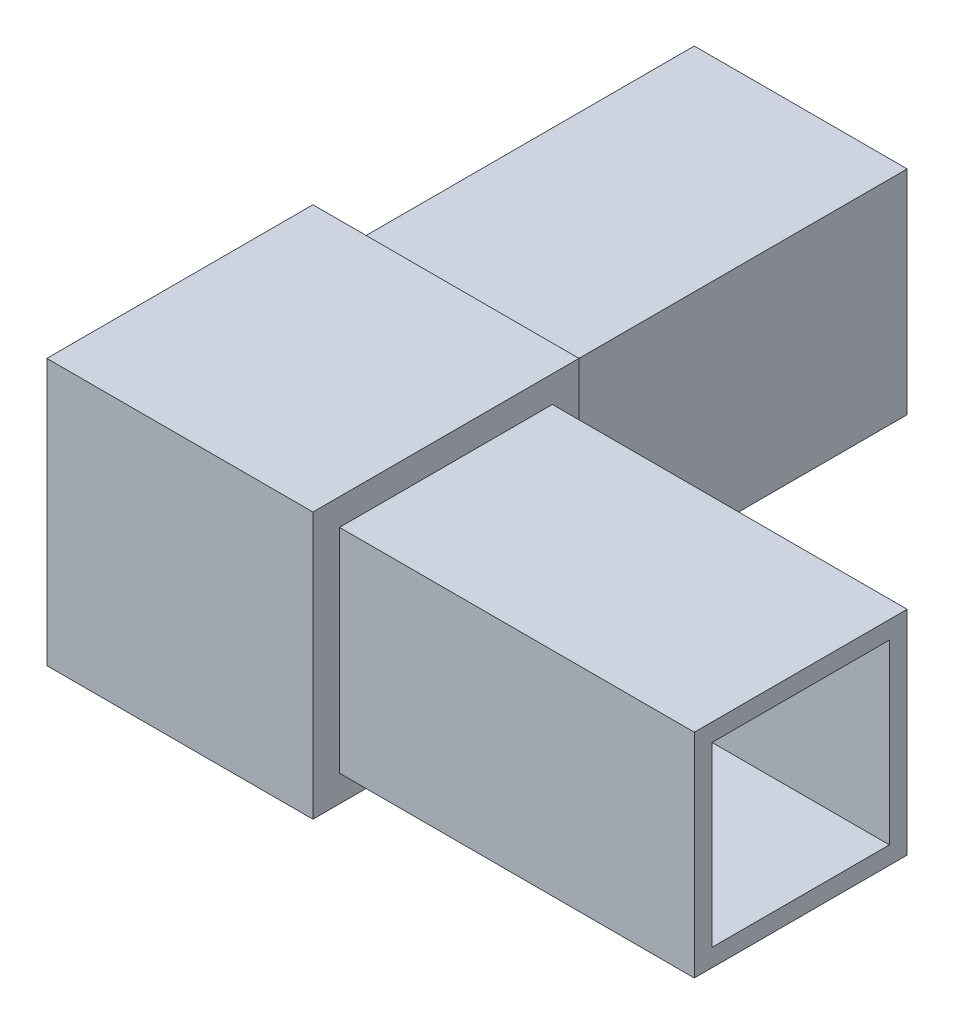
SolidWorks part; units mm, degrees
ref_plane "Alzado" through (0, 0, 0) normal (0, 0, 1) x (1, 0, 0)
ref_plane "Planta" through (0, 0, 0) normal (0, 1, 0) x (1, 0, 0)
ref_plane "Vista lateral" through (0, 0, 0) normal (1, 0, 0) x (0, 0, -1)
sketch "Croquis1" plane through (0, 0, 0) normal (0, 1, 0) x (1, 0, 0)
  line L1 (15, -15) -> (-15, -15)
  line L2 (15, -15) -> (15, 15)
  line L3 (15, 15) -> (-15, 15)
  line L4 (-15, -15) -> (-15, 15)
  line L5 (15, -15) -> (-15, 15) construction
  line L6 (15, 15) -> (-15, -15) construction
  line L7 (15, -15) -> (55, -15)
  line L8 (15, -15) -> (15, 15)
  line L9 (15, 15) -> (55, 15)
  line L10 (55, -15) -> (55, 15)
  line L11 (-15, 15) -> (15, 15)
  line L12 (-15, 15) -> (-15, 55)
  line L13 (-15, 55) -> (15, 55)
  line L14 (15, 15) -> (15, 55)
  point P0 (0, 0)
  dimension "D1" = 30
  dimension "D2" = 30
  dimension "D3" = 40
  dimension "D4" = 40
extrude "Extruir1" add sketch "Croquis1" along normal blind 30 contours L3 L14 L13 L12 | L4 L1 L2 L3 | L7 L10 L9 L2
sketch "Croquis2" plane through (55, 0, 0) normal (1, 0, 0) x (0, 0, -1)
  line L4 (-15, 0) -> (15, 0)
  line L5 (15, 0) -> (15, 30)
  line L6 (15, 30) -> (-15, 30)
  line L7 (-15, 30) -> (-15, 0)
  line L8 (-15, 0) -> (15, 0)
  line L9 (15, 0) -> (15, 30)
  line L10 (15, 30) -> (-15, 30)
  line L11 (-15, 30) -> (-15, 0)
  line L16 (-12, 3) -> (12, 3)
  line L17 (12, 3) -> (12, 27)
  line L18 (12, 27) -> (-12, 27)
  line L19 (-12, 27) -> (-12, 3)
  line L20 (-12, 3) -> (12, 3)
  line L21 (12, 3) -> (12, 27)
  line L22 (12, 27) -> (-12, 27)
  line L23 (-12, 27) -> (-12, 3)
  dimension "D1" = 0
  dimension "D2" = 3
extrude "Extruir2" cut sketch "Croquis2" against normal blind 40
sketch "Croquis3" plane through (0, 0, -55) normal (0, 0, -1) x (-1, 0, 0)
  line L0 (-12, 3) -> (12, 3)
  line L1 (12, 3) -> (12, 27)
  line L2 (12, 27) -> (-12, 27)
  line L3 (-12, 27) -> (-12, 3)
  line L4 (-15, 0) -> (15, 0)
  line L5 (15, 0) -> (15, 30)
  line L6 (15, 30) -> (-15, 30)
  line L7 (-15, 30) -> (-15, 0)
  line L8 (-15, 0) -> (15, 0)
  line L9 (15, 0) -> (15, 30)
  line L10 (15, 30) -> (-15, 30)
  line L11 (-15, 30) -> (-15, 0)
  dimension "D1" = 0
  dimension "D2" = 3
extrude "Extruir3" cut sketch "Croquis3" against normal blind 40
shell "Vaciado1" thickness 2
